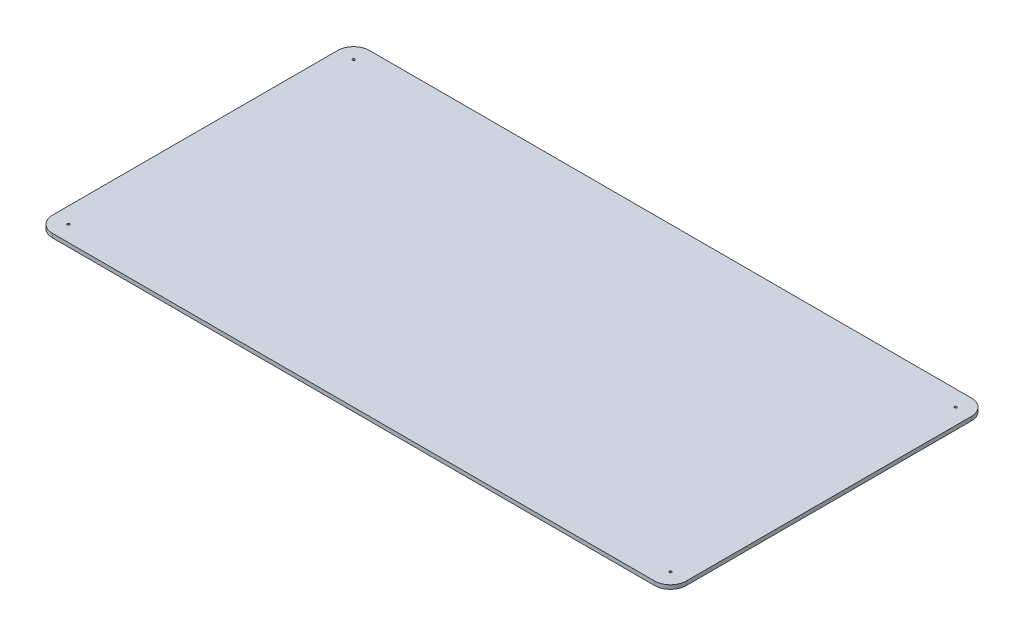
SolidWorks part; units mm, degrees
ref_plane "Front Plane" through (0, 0, 0) normal (0, 0, 1) x (1, 0, 0)
ref_plane "Top Plane" through (0, 0, 0) normal (0, 1, 0) x (1, 0, 0)
ref_plane "Right Plane" through (0, 0, 0) normal (1, 0, 0) x (0, 0, -1)
sketch "Sketch1" plane through (0, 0, 0) normal (0, 1, 0) x (1, 0, 0)
  line L1 (0, 0) -> (800, 0)
  line L2 (0, 0) -> (0, 400)
  line L3 (0, 400) -> (800, 400)
  line L4 (800, 0) -> (800, 400)
  dimension "D1" = 800
  dimension "D2" = 400
extrude "Boss-Extrude1" add sketch "Sketch1" along normal blind 5
fillet "Fillet1" radius 20 4 edges at (800, 2.5, -400) (800, 2.5, 0) (0, 2.5, 0) (0, 2.5, -400)
sketch "Sketch2" plane through (0, 5, 0) normal (0, 1, 0) x (1, 0, 0)
  line L0 (400, 400) -> (400, 0) construction
  line L1 (780, 400) -> (20, 400) construction
  line L2 (20, 0) -> (780, 0) construction
  line L3 (400, 0) -> (0, 200) construction
  line L4 (0, 380) -> (0, 20) construction
  line L5 (0, 200) -> (800, 200) construction
  line L6 (800, 20) -> (800, 380) construction
  circle A0 centre (20, 380) radius 1.5
  circle A1 centre (780, 380) radius 1.5
  circle A2 centre (780, 20) radius 1.5
  circle A3 centre (20, 20) radius 1.5
  dimension "D1" = 3
extrude "Cut-Extrude1" cut sketch "Sketch2" against normal through all
